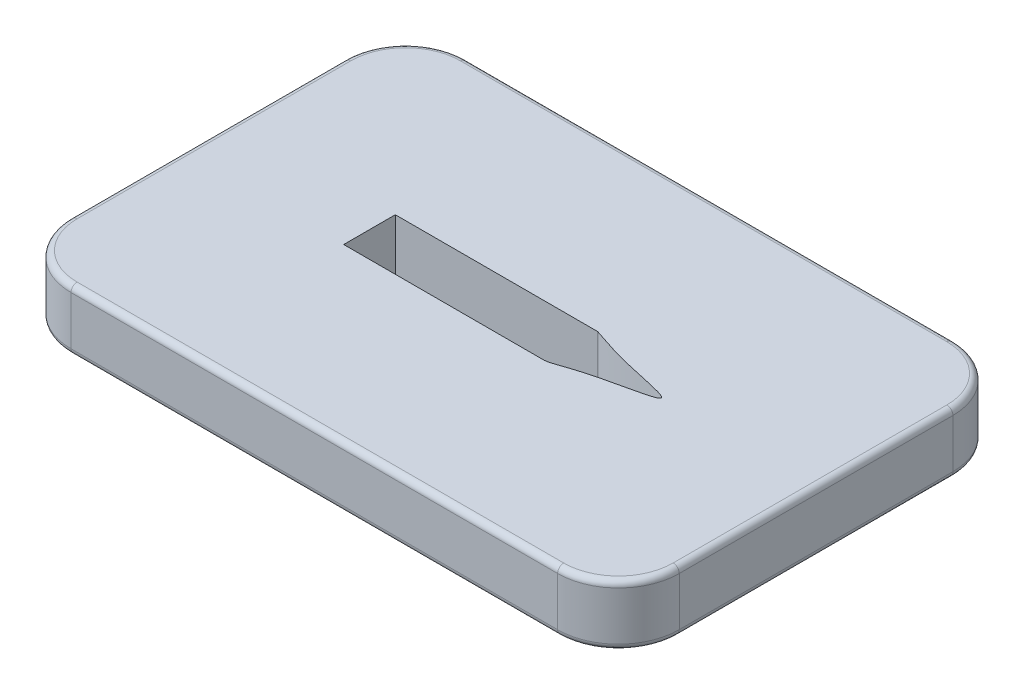
SolidWorks part; units mm, degrees
ref_plane "Front Plane" through (0, 0, 0) normal (0, 0, 1) x (1, 0, 0)
ref_plane "Top Plane" through (0, 0, 0) normal (0, 1, 0) x (1, 0, 0)
ref_plane "Right Plane" through (0, 0, 0) normal (1, 0, 0) x (0, 0, -1)
sketch "Sketch1" plane through (0, 0, 0) normal (0, 1, 0) x (1, 0, 0)
  line L0 (-62.947, 26.4706) -> (-62.947, -38.5294) construction
  line L1 (-102.947, 26.4706) -> (-22.947, 26.4706)
  line L2 (-112.947, 16.4706) -> (-112.947, -28.5294)
  line L3 (-102.947, -38.5294) -> (-22.947, -38.5294)
  line L4 (-12.947, 16.4706) -> (-12.947, -28.5294)
  line L5 (-112.947, -6.0294) -> (-12.947, -6.0294) construction
  arc A0 (-22.947, 26.4706) -> (-12.947, 16.4706) centre (-22.947, 16.4706) cw
  arc A1 (-112.947, -28.5294) -> (-102.947, -38.5294) centre (-102.947, -28.5294) ccw
  arc A2 (-102.947, 26.4706) -> (-112.947, 16.4706) centre (-102.947, 16.4706) ccw
  arc A3 (-22.947, -38.5294) -> (-12.947, -28.5294) centre (-22.947, -28.5294) ccw
  point P6 (-12.947, 26.4706)
  point P9 (-112.947, -38.5294)
  point P12 (-112.947, 26.4706)
  dimension "D3" = 10
  dimension "D4" = 10
  dimension "D5" = 10
  dimension "D6" = 10
  dimension "D1" = 100
  dimension "D2" = 65
extrude "Boss-Extrude1" add sketch "Sketch1" along normal blind 10
sketch "Sketch2" plane through (0, 10, 0) normal (0, 1, 0) x (1, 0, 0)
  line L0 (-62.947, 26.4706) -> (-62.947, -38.5294) construction
  line L1 (-22.947, 26.4706) -> (-102.947, 26.4706) construction
  line L2 (-102.947, -38.5294) -> (-22.947, -38.5294) construction
  line L3 (-112.947, -6.0294) -> (-12.947, -6.0294) construction
  line L4 (-112.947, 16.4706) -> (-112.947, -28.5294) construction
  line L5 (-12.947, -28.5294) -> (-12.947, 16.4706) construction
  line L7 (-86.3742, -1.7855) -> (-53.1559, -1.7855)
  line L8 (-86.3742, -1.7855) -> (-86.3742, -10.2733)
  line L9 (-86.3742, -10.2733) -> (-53.4231, -10.2733)
  spline S0 degree 3 poles (-53.1559, -1.7855) (-53.1291, -1.7894) (-53.1023, -1.7933) (-53.0756, -1.7972) knots 0 0 0 0 0.000996 0.000996 0.000996 0.000996
  spline S1 degree 3 poles (-53.0756, -1.7972) (-51.5415, -2.3167) (-45.4156, -4.4224) (-33.3212, -6.0152) (-45.2496, -7.6394) (-51.2515, -9.6785) (-52.6936, -10.1674) knots 0 0 0 0 0.063345 0.236845 0.409375 0.468351 0.468351 0.468351 0.468351
  spline S2 degree 3 poles (-52.6936, -10.1674) (-52.9331, -10.2067) (-53.1754, -10.2421) (-53.4231, -10.2733) knots 0.314144 0.314144 0.314144 0.314144 0.323514 0.323514 0.323514 0.323514
  point P12 (-62.947, -6.0294)
  point P17 (-39.5199, -5.7332)
  point P19 (-38.4248, -6.0294)
extrude "Cut-Extrude2" cut sketch "Sketch2" against normal blind 10 contours L7 S0 S1 S2 L9 L8
fillet "Fillet1" radius 1 8 edges at (-110.0181, 10, 35.6005) (-112.947, 10, 6.0294) (-110.0181, 10, -23.5417) (-62.947, 10, -26.4706) (-15.876, 10, -23.5417) (-12.947, 10, 6.0294) (-15.876, 10, 35.6005) (-62.947, 10, 38.5294)
fillet "Fillet2" radius 1 8 edges at (-15.876, 0, -23.5417) (-12.947, 0, 6.0294) (-15.876, 0, 35.6005) (-62.947, 0, 38.5294) (-110.0181, 0, 35.6005) (-112.947, 0, 6.0294) (-110.0181, 0, -23.5417) (-62.947, 0, -26.4706)
sketch "Sketch5" plane through (-86.3742, 0, 0) normal (1, 0, 0) x (0, 0, -1)
  point P0 (-27.1247, -3.3002)
sketch "Sketch8" plane through (0, 10, 0) normal (0, 1, 0) x (1, 0, 0)
  line L0 (-38.4306, -1.7442) -> (-38.4306, -10.2319)
  line L1 (-86.3742, -1.7855) -> (-86.3742, -10.2733) construction
  line L2 (-86.3742, -1.7855) -> (-53.1559, -1.7855) construction
  line L3 (-86.3742, -10.2733) -> (-53.4231, -10.2733) construction
  dimension "D1" = 47.9435
  dimension "D2" = 8.4878
sketch "Sketch12" plane through (0, 10, 0) normal (0, 1, 0) x (1, 0, 0)
  line L0 (-53.4231, -10.2733) -> (-52.6936, -10.2733)
  line L2 (-52.6936, -10.1674) -> (-52.6936, -10.2733)
  line L3 (-53.1559, -1.7855) -> (-53.0756, -1.7855)
  line L5 (-22.947, 25.4706) -> (-102.947, 25.4706) construction
  line L6 (-86.3742, -1.7855) -> (-53.1559, -1.7855) construction
  line L7 (-53.0756, -1.7972) -> (-53.0756, -1.7855)
  dimension "D3" = 0.0117
  dimension "D1" = 0.7296
  dimension "D2" = 0.1059
  dimension "D4" = 0.0803
